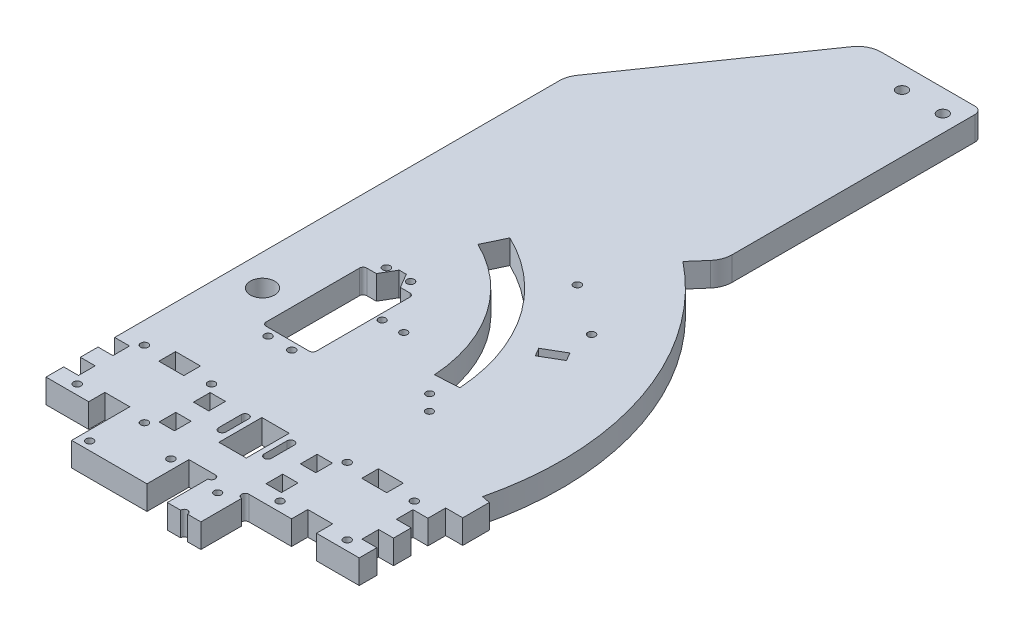
SolidWorks part; units mm, degrees
ref_plane "Płaszczyzna przednia" through (0, 0, 0) normal (0, 0, 1) x (1, 0, 0)
ref_plane "Płaszczyzna górna" through (0, 0, 0) normal (0, 1, 0) x (1, 0, 0)
ref_plane "Płaszczyzna prawa" through (0, 0, 0) normal (1, 0, 0) x (0, 0, -1)
sketch "Szkic1" plane through (0, 0, 0) normal (0, 1, 0) x (1, 0, 0)
  line L1 (0, 0) -> (100, 0)
  line L2 (0, 0) -> (0, 195)
  line L3 (0, 195) -> (100, 195)
  line L4 (100, 0) -> (100, 195)
  dimension "D1" = 100
  dimension "D2" = 195
extrude "Dodanie-wyciągnięcie1" add sketch "Szkic1" along normal blind 10
other "Przenieś ścianę2" face at (50, 5, 0) parameters "D1"=90
other "Przenieś ścianę3" face at (50, 5, -195) parameters "D1"=6.5
sketch "Szkic5" plane through (0, 0, 0) normal (0, -1, 0) x (1, 0, 0)
  line L0 (0, 90) -> (0, -201.5)
  line L1 (0, 90) -> (-538.8713, 90)
  line L2 (0, -201.5) -> (-538.8713, -201.5)
  line L3 (-538.8713, 90) -> (-538.8713, -201.5)
extrude "Dodanie-wyciągnięcie2" add sketch "Szkic5" against normal blind 10
sketch "Szkic6" plane through (0, 10, 0) normal (0, 1, 0) x (1, 0, 0)
  line L0 (100, 201.5) -> (-404.281, 201.5)
  line L1 (100, 201.5) -> (100, -91.9788)
  line L2 (-404.281, 201.5) -> (-404.281, -91.9788)
  line L3 (100, -91.9788) -> (-404.281, -91.9788)
  line L4 (100, 201.5) -> (-538.8713, 201.5) construction
extrude "Wytnij-wyciągnięcie1" cut sketch "Szkic6" against normal blind 10
sketch "Szkic3" plane through (0, 0, 0) normal (0, -1, 0) x (1, 0, 0)
  line L0 (-404.281, -201.5) -> (-404.281, -3.8665)
  line L1 (-486.6766, -104.9667) -> (-486.6766, -201.5)
  line L2 (-486.6766, -201.5) -> (-404.281, -201.5)
  line L5 (-404.281, -201.5) -> (-538.8713, -201.5) construction
  arc A0 (-486.6766, -104.9667) -> (-404.281, -3.8665) centre (-527.8713, 12.7324) ccw
  point P0 (-400.1454, 18.7324)
  dimension "D1" = 249.4
extrude "Wytnij-wyciągnięcie2" cut sketch "Szkic3" against normal blind 10
sketch "Szkic9" plane through (0, 0, 0) normal (0, -1, 0) x (1, 0, 0)
  line L4 (-494.3713, -14.7428) -> (-494.3713, 23.2572) construction
  line L5 (-495.3713, 24.2572) -> (-513.3713, 24.2572) construction
  line L6 (-514.3713, 23.2572) -> (-514.3713, -14.7428) construction
  line L7 (-513.3713, -15.7428) -> (-495.3713, -15.7428) construction
  line L8 (-494.3713, -14.7428) -> (-494.3713, 23.2572)
  line L9 (-495.3713, 24.2572) -> (-513.3713, 24.2572)
  line L10 (-514.3713, 23.2572) -> (-514.3713, -14.7428)
  line L11 (-513.3713, -15.7428) -> (-495.3713, -15.7428)
  line L60 (-513.3713, -16.2428) -> (-495.3713, -16.2428)
  line L61 (-493.8713, -14.7428) -> (-493.8713, 23.2572)
  line L62 (-495.3713, 24.7572) -> (-513.3713, 24.7572)
  line L63 (-514.8713, 23.2572) -> (-514.8713, -14.7428)
  arc A0 (-510.7148, 31.1366) -> (-508.0205, 31.1366) centre (-509.3676, 28.9342) ccw construction
  arc A1 (-500.6957, 31.1375) -> (-498.0469, 31.1375) centre (-499.3713, 29.0172) ccw construction
  arc A2 (-508.0205, -22.6222) -> (-510.7148, -22.6222) centre (-509.3676, -20.4199) ccw construction
  arc A3 (-498.0469, -22.6232) -> (-500.6957, -22.6232) centre (-499.3713, -20.5028) ccw construction
  arc A4 (-510.7148, 31.1366) -> (-508.0205, 31.1366) centre (-509.3676, 28.9342) ccw
  arc A5 (-500.6957, 31.1375) -> (-498.0469, 31.1375) centre (-499.3713, 29.0172) ccw
  arc A6 (-508.0205, -22.6222) -> (-510.7148, -22.6222) centre (-509.3676, -20.4199) ccw
  arc A7 (-498.0469, -22.6232) -> (-500.6957, -22.6232) centre (-499.3713, -20.5028) ccw
  circle A8 centre (-499.3713, 29.0172) radius 1.55
  circle A9 centre (-509.3676, 28.9342) radius 1.55
  circle A10 centre (-499.3713, -20.5028) radius 1.55
  circle A11 centre (-509.3676, -20.4199) radius 1.55
  arc A16 (-494.3713, 23.2572) -> (-495.3713, 24.2572) centre (-495.3713, 23.2572) ccw construction
  arc A17 (-513.3713, 24.2572) -> (-514.3713, 23.2572) centre (-513.3713, 23.2572) ccw construction
  arc A18 (-495.3713, -15.7428) -> (-494.3713, -14.7428) centre (-495.3713, -14.7428) ccw construction
  arc A19 (-514.3713, -14.7428) -> (-513.3713, -15.7428) centre (-513.3713, -14.7428) ccw construction
  arc A20 (-514.3713, -14.7428) -> (-513.3713, -15.7428) centre (-513.3713, -14.7428) ccw
  arc A21 (-494.3713, 23.2572) -> (-495.3713, 24.2572) centre (-495.3713, 23.2572) ccw
  arc A22 (-513.3713, 24.2572) -> (-514.3713, 23.2572) centre (-513.3713, 23.2572) ccw
  arc A23 (-495.3713, -15.7428) -> (-494.3713, -14.7428) centre (-495.3713, -14.7428) ccw
  arc A72 (-514.3713, -14.7428) -> (-513.3713, -15.7428) centre (-513.3713, -14.7428) ccw
  arc A73 (-495.3713, -16.2428) -> (-493.8713, -14.7428) centre (-495.3713, -14.7428) ccw
  arc A74 (-493.8713, 23.2572) -> (-495.3713, 24.7572) centre (-495.3713, 23.2572) ccw
  arc A75 (-513.3713, 24.7572) -> (-514.8713, 23.2572) centre (-513.3713, 23.2572) ccw
  arc A76 (-514.8713, -14.7428) -> (-513.3713, -16.2428) centre (-513.3713, -14.7428) ccw
  dimension "D1" = 3.1
  dimension "D2" = 3.1
  dimension "D3" = 3.1
  dimension "D4" = 3.1
  dimension "D5" = 0.5
  dimension "D6" = 0.5
sketch "Szkic10" plane through (0, 0, 0) normal (0, -1, 0) x (1, 0, 0)
  line L0 (-509.3713, -16.2428) -> (-505.8713, -22.2428)
  line L1 (-513.3713, -16.2428) -> (-495.3713, -16.2428) construction
  line L2 (-493.8713, -14.7428) -> (-493.8713, 23.2572) construction
  line L4 (-514.8713, 23.2572) -> (-514.8713, -14.7428) construction
  line L5 (-513.3713, -16.2428) -> (-509.3713, -16.2428)
  line L6 (-505.8713, -22.2428) -> (-502.8713, -22.2428)
  line L7 (-493.8713, -14.7428) -> (-493.8713, 23.2572)
  line L9 (-514.8713, 23.2572) -> (-514.8713, -14.7428)
  line L10 (-502.8713, -22.2428) -> (-499.3713, -16.2428)
  line L11 (-499.3713, -16.2428) -> (-495.3713, -16.2428)
  line L12 (-513.3713, 25.7572) -> (-495.3713, 25.7572)
  line L13 (-493.8713, 23.2572) -> (-493.8713, 24.2572)
  line L14 (-514.8713, 23.2572) -> (-514.8713, 24.2572)
  circle A0 centre (-499.3713, -20.5028) radius 1.55 construction
  circle A1 centre (-509.3676, -20.4199) radius 1.55 construction
  circle A2 centre (-509.3676, 28.9342) radius 1.55 construction
  circle A3 centre (-499.3713, 29.0172) radius 1.55 construction
  circle A4 centre (-499.3713, -20.5028) radius 1.55
  circle A5 centre (-509.3676, -20.4199) radius 1.55
  circle A6 centre (-509.3676, 28.9342) radius 1.55
  circle A7 centre (-499.3713, 29.0172) radius 1.55
  arc A8 (-493.8713, 24.2572) -> (-495.3713, 25.7572) centre (-495.3713, 24.2572) ccw
  arc A9 (-514.8713, 24.2572) -> (-513.3713, 25.7572) centre (-513.3713, 24.2572) cw
  arc A10 (-495.3713, -16.2428) -> (-493.8713, -14.7428) centre (-495.3713, -14.7428) ccw construction
  arc A15 (-514.8713, -14.7428) -> (-513.3713, -16.2428) centre (-513.3713, -14.7428) ccw construction
  arc A16 (-495.3713, -16.2428) -> (-493.8713, -14.7428) centre (-495.3713, -14.7428) ccw
  arc A19 (-514.8713, -14.7428) -> (-513.3713, -16.2428) centre (-513.3713, -14.7428) ccw
  dimension "D7" = 1.5
  dimension "D1" = 5.5
  dimension "D2" = 5.5
  dimension "D3" = 6
  dimension "D4" = 3.5
  dimension "D5" = 3.5
  dimension "D6" = 42
extrude "Wytnij-wyciągnięcie5" cut sketch "Szkic10" against normal through all
ref_plane "Płaszczyzna1" through (-472.5713, 0, 0) normal (-1, 0, 0) x (0, 0, 1)
sketch "Szkic11" plane through (0, 0, 0) normal (0, -1, 0) x (1, 0, 0)
  line L4 (-494.8713, 75.8884) -> (-500.8713, 75.8884) construction
  line L5 (-500.8713, 75.8884) -> (-500.8713, 82.4384) construction
  line L6 (-500.8713, 82.4384) -> (-494.8713, 82.4384) construction
  line L7 (-494.8713, 82.4384) -> (-494.8713, 75.8884) construction
  line L9 (-522.8713, 60.55) -> (-512.8713, 60.55) construction
  line L10 (-512.8713, 60.55) -> (-512.8713, 54) construction
  line L11 (-512.8713, 54) -> (-522.8713, 54) construction
  line L12 (-500.8713, 68.1116) -> (-494.8713, 68.1116) construction
  line L13 (-494.8713, 68.1116) -> (-494.8713, 61.5616) construction
  line L14 (-494.8713, 61.5616) -> (-500.8713, 61.5616) construction
  line L15 (-500.8713, 61.5616) -> (-500.8713, 68.1116) construction
  line L16 (-522.8713, 83.45) -> (-522.8713, 90)
  line L17 (-522.8713, 90) -> (-512.8713, 90)
  line L18 (-512.8713, 90) -> (-512.8713, 83.45)
  line L19 (-512.8713, 83.45) -> (-522.8713, 83.45)
  line L20 (-494.8713, 75.8884) -> (-500.8713, 75.8884)
  line L21 (-500.8713, 75.8884) -> (-500.8713, 82.4384)
  line L22 (-500.8713, 82.4384) -> (-494.8713, 82.4384)
  line L23 (-494.8713, 82.4384) -> (-494.8713, 75.8884)
  line L24 (-522.8713, 54) -> (-522.8713, 60.55)
  line L25 (-522.8713, 60.55) -> (-512.8713, 60.55)
  line L26 (-512.8713, 60.55) -> (-512.8713, 54)
  line L27 (-512.8713, 54) -> (-522.8713, 54)
  line L28 (-500.8713, 68.1116) -> (-494.8713, 68.1116)
  line L29 (-494.8713, 68.1116) -> (-494.8713, 61.5616)
  line L30 (-494.8713, 61.5616) -> (-500.8713, 61.5616)
  line L31 (-500.8713, 61.5616) -> (-500.8713, 68.1116)
  line L32 (-534.8713, 75.8884) -> (-540.8713, 75.8884) construction
  line L33 (-540.8713, 75.8884) -> (-540.8713, 82.4384) construction
  line L34 (-540.8713, 82.4384) -> (-534.8713, 82.4384) construction
  line L35 (-534.8713, 82.4384) -> (-534.8713, 75.8884) construction
  line L36 (-540.8713, 68.1116) -> (-534.8713, 68.1116) construction
  line L37 (-534.8713, 68.1116) -> (-534.8713, 61.5616) construction
  line L38 (-534.8713, 61.5616) -> (-540.8713, 61.5616) construction
  line L39 (-540.8713, 61.5616) -> (-540.8713, 68.1116) construction
  line L40 (-534.8713, 75.8884) -> (-540.8713, 75.8884)
  line L41 (-540.8713, 75.8884) -> (-540.8713, 82.4384)
  line L42 (-540.8713, 82.4384) -> (-534.8713, 82.4384)
  line L43 (-534.8713, 82.4384) -> (-534.8713, 75.8884)
  line L44 (-540.8713, 68.1116) -> (-534.8713, 68.1116)
  line L45 (-534.8713, 68.1116) -> (-534.8713, 61.5616)
  line L46 (-534.8713, 61.5616) -> (-540.8713, 61.5616)
  line L47 (-540.8713, 61.5616) -> (-540.8713, 68.1116)
  line L48 (-523.0713, 53.8) -> (-523.0713, 60.75)
  line L49 (-523.0713, 60.75) -> (-512.6713, 60.75)
  line L50 (-512.6713, 60.75) -> (-512.6713, 53.8)
  line L51 (-512.6713, 53.8) -> (-523.0713, 53.8)
  line L52 (-534.6713, 68.3116) -> (-534.6713, 61.3616)
  line L53 (-534.6713, 61.3616) -> (-541.0713, 61.3616)
  line L54 (-541.0713, 61.3616) -> (-541.0713, 68.3116)
  line L55 (-541.0713, 68.3116) -> (-534.6713, 68.3116)
  line L56 (-534.6713, 82.6384) -> (-534.6713, 75.6884)
  line L57 (-534.6713, 75.6884) -> (-541.0713, 75.6884)
  line L58 (-541.0713, 75.6884) -> (-541.0713, 82.6384)
  line L59 (-541.0713, 82.6384) -> (-534.6713, 82.6384)
  line L60 (-523.0713, 83.25) -> (-523.0713, 90.2)
  line L61 (-523.0713, 90.2) -> (-512.6713, 90.2)
  line L62 (-512.6713, 90.2) -> (-512.6713, 83.25)
  line L63 (-512.6713, 83.25) -> (-523.0713, 83.25)
  line L64 (-501.0713, 75.6884) -> (-501.0713, 82.6384)
  line L65 (-501.0713, 82.6384) -> (-494.6713, 82.6384)
  line L66 (-494.6713, 82.6384) -> (-494.6713, 75.6884)
  line L67 (-494.6713, 75.6884) -> (-501.0713, 75.6884)
  line L68 (-501.0713, 61.3616) -> (-501.0713, 68.3116)
  line L69 (-501.0713, 68.3116) -> (-494.6713, 68.3116)
  line L70 (-494.6713, 68.3116) -> (-494.6713, 61.3616)
  line L71 (-494.6713, 61.3616) -> (-501.0713, 61.3616)
  line L72 (-522.8713, 90) -> (-522.8713, 83.45) construction
  circle A0 centre (-531.8713, 58) radius 1.55 construction
  circle A1 centre (-419.2913, 58) radius 1.55 construction
  circle A2 centre (-419.2913, 86) radius 1.55 construction
  circle A3 centre (-531.8713, 86) radius 1.55 construction
  circle A4 centre (-531.8713, 58) radius 1.55
  circle A5 centre (-419.2913, 58) radius 1.55
  circle A6 centre (-419.2913, 86) radius 1.55
  circle A7 centre (-531.8713, 86) radius 1.55
  dimension "D2" = 0
  dimension "D1" = 0.2
sketch "Szkic12" plane through (0, 0, 0) normal (0, -1, 0) x (1, 0, 0)
  line L0 (-534.6713, 68.3116) -> (-534.6713, 61.3616) construction
  line L1 (-534.6713, 61.3616) -> (-541.0713, 61.3616) construction
  line L2 (-541.0713, 61.3616) -> (-541.0713, 68.3116) construction
  line L3 (-541.0713, 68.3116) -> (-534.6713, 68.3116) construction
  line L4 (-534.6713, 82.6384) -> (-534.6713, 75.6884) construction
  line L5 (-534.6713, 75.6884) -> (-541.0713, 75.6884) construction
  line L6 (-541.0713, 75.6884) -> (-541.0713, 82.6384) construction
  line L7 (-541.0713, 82.6384) -> (-534.6713, 82.6384) construction
  line L8 (-523.0713, 53.8) -> (-523.0713, 60.75) construction
  line L9 (-523.0713, 60.75) -> (-512.6713, 60.75) construction
  line L10 (-512.6713, 60.75) -> (-512.6713, 53.8) construction
  line L11 (-512.6713, 53.8) -> (-523.0713, 53.8) construction
  line L12 (-523.0713, 83.25) -> (-523.0713, 90.2) construction
  line L13 (-523.0713, 90.2) -> (-512.6713, 90.2) construction
  line L14 (-512.6713, 90.2) -> (-512.6713, 83.25) construction
  line L15 (-512.6713, 83.25) -> (-523.0713, 83.25) construction
  line L16 (-501.0713, 61.3616) -> (-501.0713, 68.3116) construction
  line L17 (-501.0713, 68.3116) -> (-494.6713, 68.3116) construction
  line L18 (-494.6713, 68.3116) -> (-494.6713, 61.3616) construction
  line L19 (-494.6713, 61.3616) -> (-501.0713, 61.3616) construction
  line L20 (-501.0713, 75.6884) -> (-501.0713, 82.6384) construction
  line L21 (-501.0713, 82.6384) -> (-494.6713, 82.6384) construction
  line L22 (-494.6713, 82.6384) -> (-494.6713, 75.6884) construction
  line L23 (-494.6713, 75.6884) -> (-501.0713, 75.6884) construction
  line L24 (-534.6713, 68.3116) -> (-534.6713, 61.3616)
  line L25 (-534.6713, 61.3616) -> (-541.0713, 61.3616)
  line L26 (-541.0713, 61.3616) -> (-541.0713, 68.3116)
  line L27 (-541.0713, 68.3116) -> (-534.6713, 68.3116)
  line L28 (-534.6713, 82.6384) -> (-534.6713, 75.6884)
  line L29 (-534.6713, 75.6884) -> (-541.0713, 75.6884)
  line L30 (-541.0713, 75.6884) -> (-541.0713, 82.6384)
  line L31 (-541.0713, 82.6384) -> (-534.6713, 82.6384)
  line L32 (-523.0713, 53.8) -> (-523.0713, 60.75)
  line L33 (-523.0713, 60.75) -> (-512.6713, 60.75)
  line L34 (-512.6713, 60.75) -> (-512.6713, 53.8)
  line L35 (-512.6713, 53.8) -> (-523.0713, 53.8)
  line L36 (-523.0713, 83.25) -> (-523.0713, 90.2)
  line L37 (-523.0713, 90.2) -> (-512.6713, 90.2)
  line L38 (-512.6713, 90.2) -> (-512.6713, 83.25)
  line L39 (-512.6713, 83.25) -> (-523.0713, 83.25)
  line L40 (-501.0713, 61.3616) -> (-501.0713, 68.3116)
  line L41 (-501.0713, 68.3116) -> (-494.6713, 68.3116)
  line L42 (-494.6713, 68.3116) -> (-494.6713, 61.3616)
  line L43 (-494.6713, 61.3616) -> (-501.0713, 61.3616)
  line L44 (-501.0713, 75.6884) -> (-501.0713, 82.6384)
  line L45 (-501.0713, 82.6384) -> (-494.6713, 82.6384)
  line L46 (-494.6713, 82.6384) -> (-494.6713, 75.6884)
  line L47 (-494.6713, 75.6884) -> (-501.0713, 75.6884)
  line L48 (-475.5761, 90) -> (-475.5761, 36.9235) construction
  line L50 (-456.481, 75.6884) -> (-450.081, 75.6884)
  line L51 (-456.481, 82.6384) -> (-456.481, 75.6884)
  line L52 (-450.081, 82.6384) -> (-456.481, 82.6384)
  line L53 (-450.081, 75.6884) -> (-450.081, 82.6384)
  line L54 (-456.481, 61.3616) -> (-450.081, 61.3616)
  line L55 (-456.481, 68.3116) -> (-456.481, 61.3616)
  line L56 (-450.081, 68.3116) -> (-456.481, 68.3116)
  line L57 (-450.081, 61.3616) -> (-450.081, 68.3116)
  line L58 (-438.481, 83.25) -> (-428.081, 83.25)
  line L59 (-438.481, 90.2) -> (-438.481, 83.25)
  line L60 (-428.081, 90.2) -> (-438.481, 90.2)
  line L61 (-428.081, 83.25) -> (-428.081, 90.2)
  line L62 (-438.481, 53.8) -> (-428.081, 53.8)
  line L63 (-438.481, 60.75) -> (-438.481, 53.8)
  line L64 (-428.081, 60.75) -> (-438.481, 60.75)
  line L65 (-428.081, 53.8) -> (-428.081, 60.75)
  line L66 (-410.081, 82.6384) -> (-416.481, 82.6384)
  line L67 (-410.081, 75.6884) -> (-410.081, 82.6384)
  line L68 (-416.481, 75.6884) -> (-410.081, 75.6884)
  line L69 (-416.481, 82.6384) -> (-416.481, 75.6884)
  line L70 (-410.081, 68.3116) -> (-416.481, 68.3116)
  line L71 (-410.081, 61.3616) -> (-410.081, 68.3116)
  line L72 (-416.481, 61.3616) -> (-410.081, 61.3616)
  line L73 (-416.481, 68.3116) -> (-416.481, 61.3616)
  line L74 (-538.8713, 90) -> (-538.8713, -201.5) construction
  circle A4 centre (-419.2913, 86) radius 1.55 construction
  circle A5 centre (-419.2913, 58) radius 1.55 construction
  circle A6 centre (-531.8713, 86) radius 1.55 construction
  circle A7 centre (-531.8713, 58) radius 1.55 construction
  circle A8 centre (-419.2913, 86) radius 1.55
  circle A9 centre (-419.2913, 58) radius 1.55
  circle A10 centre (-531.8713, 86) radius 1.55
  circle A11 centre (-531.8713, 58) radius 1.55
  circle A12 centre (-447.2913, 86) radius 1.55 construction
  circle A13 centre (-447.2913, 58) radius 1.55 construction
  circle A14 centre (-503.8713, 58) radius 1.55 construction
  circle A15 centre (-503.8713, 86) radius 1.55 construction
  circle A16 centre (-447.2913, 86) radius 1.55
  circle A17 centre (-447.2913, 58) radius 1.55
  circle A18 centre (-503.8713, 58) radius 1.55
  circle A19 centre (-503.8713, 86) radius 1.55
  dimension "D1" = 63.2952
extrude "Wytnij-wyciągnięcie6" cut sketch "Szkic12" against normal blind 10
sketch "Szkic13" plane through (0, 10, 0) normal (0, 1, 0) x (1, 0, 0)
  line L2 (-467.6261, -67.3) -> (-467.6261, -61.3) construction
  line L3 (-467.6261, -75.3) -> (-467.6261, -69.3) construction
  line L4 (-464.5261, -61.3) -> (-464.5261, -67.3) construction
  line L5 (-464.5261, -69.3) -> (-464.5261, -75.3) construction
  line L6 (-470.0761, -61.3) -> (-481.0761, -61.3) construction
  line L7 (-481.0761, -75.3) -> (-470.0761, -75.3) construction
  line L8 (-467.6261, -67.3) -> (-467.6261, -61.3)
  line L9 (-467.6261, -75.3) -> (-467.6261, -69.3)
  line L10 (-464.5261, -61.3) -> (-464.5261, -67.3)
  line L11 (-464.5261, -69.3) -> (-464.5261, -75.3)
  line L12 (-470.0761, -61.3) -> (-481.0761, -61.3)
  line L13 (-481.0761, -75.3) -> (-470.0761, -75.3)
  line L14 (-467.6261, -72.3) -> (-464.5261, -72.3)
  line L15 (-467.6261, -64.3) -> (-464.5261, -64.3)
  line L16 (-481.0761, -75.3) -> (-481.0761, -61.3)
  line L21 (-467.6261, -72.3) -> (-467.6261, -64.3)
  line L22 (-464.5261, -76.9028) -> (-464.5261, -68.9108)
  line L23 (-470.0761, -75.3) -> (-470.0761, -61.3)
  line L24 (-481.2761, -75.5) -> (-469.8761, -75.5)
  line L25 (-469.8761, -75.5) -> (-469.8761, -61.1)
  line L26 (-469.8761, -61.1) -> (-481.2761, -61.1)
  line L27 (-481.2761, -75.5) -> (-481.2761, -61.1)
  line L28 (-486.6261, -69.3) -> (-486.6261, -75.3) construction
  line L29 (-483.5261, -69.3) -> (-483.5261, -75.3) construction
  line L30 (-486.6261, -61.3) -> (-486.6261, -67.3) construction
  line L31 (-483.5261, -61.3) -> (-483.5261, -67.3) construction
  line L32 (-486.6261, -69.3) -> (-486.6261, -75.3)
  line L33 (-483.5261, -69.3) -> (-483.5261, -75.3)
  line L34 (-486.6261, -61.3) -> (-486.6261, -67.3)
  line L35 (-483.5261, -61.3) -> (-483.5261, -67.3)
  line L36 (-486.6261, -72.3) -> (-483.5261, -72.3)
  line L37 (-486.6261, -64.3) -> (-483.5261, -64.3)
  circle A0 centre (-466.0761, -72.3) radius 1.55
  circle A1 centre (-466.0761, -64.3) radius 1.55
  circle A2 centre (-464.5305, -14.7117) radius 10.0739
  circle A3 centre (-485.0761, -72.3) radius 1.55
  circle A4 centre (-485.0761, -64.3) radius 1.55
  dimension "D1" = 3.1
  dimension "D2" = 3.1
  dimension "D4" = 3.1
  dimension "D5" = 3.1
  dimension "D3" = 0.2
sketch "Szkic14" plane through (0, 10, 0) normal (0, 1, 0) x (1, 0, 0)
  line L0 (-469.8761, -75.5) -> (-469.8761, -77.5)
  line L1 (-481.2761, -77.5) -> (-469.8761, -77.5)
  line L2 (-486.6261, -64.3) -> (-486.6261, -62.8)
  line L3 (-483.5261, -64.3) -> (-483.5261, -62.8)
  line L4 (-481.2761, -75.5) -> (-481.2761, -61.1) construction
  line L6 (-469.8761, -75.5) -> (-469.8761, -61.1) construction
  line L7 (-467.6261, -64.3) -> (-467.6261, -62.8)
  line L8 (-467.6261, -72.3) -> (-467.6261, -64.3) construction
  line L9 (-464.5261, -76.9028) -> (-464.5261, -68.9108) construction
  line L10 (-467.6261, -72.3) -> (-467.6261, -64.3)
  line L11 (-464.5261, -72.3) -> (-464.5261, -64.3)
  line L12 (-481.2761, -75.5) -> (-481.2761, -61.1)
  line L13 (-481.2761, -61.1) -> (-481.2761, -59.6)
  line L14 (-469.8761, -75.5) -> (-469.8761, -61.1)
  line L15 (-481.2761, -77.5) -> (-481.2761, -75.5)
  line L16 (-486.6261, -72.3) -> (-486.6261, -64.3)
  line L17 (-483.5261, -72.3) -> (-483.5261, -64.3)
  line L18 (-464.5261, -64.3) -> (-464.5261, -62.8)
  line L19 (-469.8761, -59.6) -> (-481.2761, -59.6)
  line L20 (-469.8761, -59.6) -> (-469.8761, -61.1)
  circle A0 centre (-466.0761, -72.3) radius 1.55 construction
  circle A1 centre (-485.0761, -72.3) radius 1.55 construction
  arc A2 (-467.6261, -72.3) -> (-464.5261, -72.3) centre (-466.0761, -72.3) ccw
  circle A5 centre (-485.0761, -64.3) radius 1.55 construction
  arc A6 (-486.6261, -72.3) -> (-483.5261, -72.3) centre (-485.0761, -72.3) ccw
  circle A7 centre (-466.0761, -64.3) radius 1.55 construction
  arc A8 (-483.5261, -62.8) -> (-486.6261, -62.8) centre (-485.0761, -62.8) ccw
  arc A9 (-464.5261, -62.8) -> (-467.6261, -62.8) centre (-466.0761, -62.8) ccw
  dimension "D1" = 1.5
  dimension "D2" = 1.5
  dimension "D3" = 1.5
  dimension "D4" = 2
extrude "Wytnij-wyciągnięcie7" cut sketch "Szkic14" against normal blind 10
sketch "Szkic15" plane through (0, 0, 0) normal (0, -1, 0) x (-1, 0, 0)
  line L0 (475.5761, -90) -> (475.5761, -31.9756) construction
  line L1 (512.6713, -90) -> (438.481, -90) construction
  line L2 (475.5761, -31.9756) -> (475.5761, -90) construction
sketch "Szkic16" plane through (0, 0, 0) normal (0, -1, 0) x (1, 0, 0)
  line L0 (-460.7106, 8.2055) -> (-450.7332, 7.5329)
  line L1 (-498.7398, -47.9505) -> (-494.4121, -56.9655)
  arc A2 (-494.4121, -56.9655) -> (-450.7332, 7.5329) centre (-527.8713, 12.7324) ccw
  arc A3 (-498.7398, -47.9505) -> (-460.7106, 8.2055) centre (-527.8713, 12.7324) ccw
  point P0 (-527.8713, 12.7324)
  point P1 (-527.8713, 12.7324)
  point P2 (-492.681, -60.5715)
  point P3 (-496.1432, -53.3595)
  point P4 (-456.1497, 27.9252)
  point P5 (-448.3233, 29.5831)
extrude "Wytnij-wyciągnięcie8" cut sketch "Szkic16" against normal blind 10
sketch "Szkic17" plane through (0, 0, 0) normal (0, -1, 0) x (1, 0, 0)
  line L0 (-470.2913, 90) -> (-456.2913, 90)
  line L1 (-470.2913, 90) -> (-470.2913, 110)
  line L2 (-456.2913, 90) -> (-456.2913, 110)
  line L3 (-470.2913, 110) -> (-456.2913, 110)
  line L4 (-512.6713, 90) -> (-438.481, 90) construction
  line L5 (-456.2913, 90) -> (-456.2913, 82.4384) construction
  line L6 (-481.2761, 107.5) -> (-512.6713, 107.5)
  line L7 (-481.2761, 90) -> (-512.6713, 90)
  line L8 (-481.2761, 90) -> (-481.2761, 107.5)
  line L9 (-512.6713, 90) -> (-512.6713, 107.5)
  line L13 (-512.6713, 83.25) -> (-512.6713, 90) construction
  dimension "D1" = 0
  dimension "D2" = 20
  dimension "D3" = 14
  dimension "D4" = 17.5
  dimension "D5" = 31.3952
  dimension "D6" = 0
extrude "Dodanie-wyciągnięcie3" add sketch "Szkic17" against normal blind 10
sketch "Szkic18" plane through (0, 0, 0) normal (0, -1, 0) x (1, 0, 0)
  circle A1 centre (-450.9064, -49.5364) radius 3
sketch "Szkic19" plane through (0, 0, 0) normal (0, -1, 0) x (1, 0, 0)
  circle A0 centre (-527.8713, 12.7324) radius 5.05 construction
  circle A1 centre (-527.8713, 12.7324) radius 5.05
extrude "Wytnij-wyciągnięcie10" cut sketch "Szkic19" against normal blind 10
sketch "Szkic20" plane through (0, 0, 0) normal (0, -1, 0) x (1, 0, 0)
  line L0 (-538.8713, 53.8) -> (-538.9213, 53.8)
  line L1 (-538.8713, 61.3616) -> (-538.8713, -201.5) construction
  line L2 (-540.8713, 51.85) -> (-540.8713, -199.55)
  line L3 (-538.9213, -201.5) -> (-538.8713, -201.5)
  line L4 (-538.8713, -201.5) -> (-538.8713, 53.8)
  line L5 (-523.0713, 53.8) -> (-512.6713, 53.8) construction
  arc A0 (-540.8713, -199.55) -> (-538.9213, -201.5) centre (-538.9213, -199.55) ccw
  arc A1 (-538.9213, 53.8) -> (-540.8713, 51.85) centre (-538.9213, 51.85) ccw
  dimension "D3" = 1.95
  dimension "D1" = 2
  dimension "D2" = 0
extrude "Dodanie-wyciągnięcie4" add sketch "Szkic20" against normal blind 10 separate body
combine bodies "Połącz1" operation type add bodies to combine 124 123
sketch "Szkic22" plane through (0, 10, 0) normal (0, 1, 0) x (1, 0, 0)
  line L0 (-486.6766, 201.5) -> (-477.6766, 201.5)
  line L1 (-475.6766, 199.5) -> (-475.6766, 114.8256)
  line L2 (-440.9781, 88.2026) -> (-440.0828, 89.1525)
  line L3 (-486.6766, 104.9667) -> (-486.6766, 201.5)
  line L8 (-440.9781, 88.2026) -> (-448.3145, 80.4192)
  line L9 (-448.3145, 80.4192) -> (-486.6766, 104.9667)
  arc A0 (-404.281, 3.8665) -> (-486.6766, 104.9667) centre (-527.8713, -12.7324) ccw construction
  arc A1 (-477.6766, 201.5) -> (-475.6766, 199.5) centre (-477.6766, 199.5) cw
  arc A2 (-474.4586, 112.9848) -> (-475.6766, 114.8256) centre (-473.6766, 114.8256) cw
  arc A3 (-440.0828, 89.1525) -> (-440.2553, 92.0587) centre (-441.5381, 90.5243) ccw
  arc A4 (-474.4586, 112.9848) -> (-440.2553, 92.0587) centre (-527.8713, -12.7324) cw
  point P18 (-440.2504, 87.5167)
  point P20 (-452.5967, 74.4182)
  point P22 (-453.3244, 75.1041)
  dimension "D2" = 2
  dimension "D3" = 2
  dimension "D4" = 2
  dimension "D1" = 11
extrude "Dodanie-wyciągnięcie5" add sketch "Szkic22" against normal blind 10
sketch "Szkic23" plane through (0, 0, 0) normal (0, -1, 0) x (-1, 0, 0)
  line L0 (538.8713, -90) -> (540.8713, -90)
  line L1 (540.8713, -90) -> (540.8713, -82.6384)
  line L2 (540.8713, -82.6384) -> (538.8713, -82.6384)
  line L3 (538.8713, -82.6384) -> (538.8713, -90)
  line L4 (538.8713, -75.6884) -> (540.8713, -75.6884)
  line L5 (538.8713, -75.6884) -> (538.8713, -68.3116)
  line L6 (540.8713, -75.6884) -> (540.8713, -68.3116)
  line L7 (538.8713, -68.3116) -> (540.8713, -68.3116)
  line L8 (538.8713, -61.3616) -> (540.8713, -61.3616)
  line L9 (540.8713, -61.3616) -> (540.8713, -51.85)
  line L10 (540.8713, -51.85) -> (538.8713, -53.8)
  line L11 (538.8713, -53.8) -> (538.8713, -61.3616)
  line L12 (534.6713, -68.3116) -> (538.8713, -68.3116) construction
  dimension "D1" = 0
extrude "Dodanie-wyciągnięcie6" add sketch "Szkic23" against normal blind 10
sketch "Szkic24" plane through (0, 10, 0) normal (0, 1, 0) x (1, 0, 0)
  arc A0 (-404.281, 3.8665) -> (-409.8648, -53.0383) centre (-527.8713, -12.7324) cw
sketch "Szkic25" plane through (0, 10, 0) normal (0, 1, 0) x (1, 0, 0)
  line L0 (-404.281, 3.8665) -> (-404.281, -29.3314)
  arc A0 (-409.8648, -53.0383) -> (-404.281, 3.8665) centre (-527.8713, -12.7324) ccw construction
  arc A1 (-404.281, -29.3314) -> (-404.281, 3.8665) centre (-527.8713, -12.7324) ccw
extrude "Dodanie-wyciągnięcie7" add sketch "Szkic25" against normal blind 10
sketch "Szkic26" plane through (0, 10, 0) normal (0, 1, 0) x (1, 0, 0)
  line L0 (-399.9995, -49.9762) -> (-396.142, -50.9135)
  line L3 (-404.281, -29.3314) -> (-395.7395, -31.6227)
  line L4 (-395.7395, -31.6227) -> (-396.142, -50.9135)
  line L7 (-399.9995, -49.9762) -> (-408.2538, -47.9707)
  arc A0 (-409.8648, -53.0383) -> (-404.281, 3.8665) centre (-527.8713, -12.7324) ccw construction
  arc A4 (-408.2538, -47.9707) -> (-404.281, -29.3314) centre (-527.8713, -12.7324) ccw
  point P1 (-399.7634, -49.0045)
  point P11 (-417.2545, -44.7547)
extrude "Wytnij-wyciągnięcie14" cut sketch "Szkic26" against normal blind 10
sketch "Szkic27" plane through (0, 0, 0) normal (0, -1, 0) x (1, 0, 0)
  circle A0 centre (-508.6761, 104) radius 1.55 construction
  circle A1 centre (-485.2761, 93.5) radius 1.55 construction
  circle A2 centre (-508.6761, 104) radius 1.55
  circle A3 centre (-485.2761, 93.5) radius 1.55
extrude "Wytnij-wyciągnięcie15" cut sketch "Szkic27" against normal blind 10
sketch "Szkic28" plane through (0, 10, 0) normal (0, 1, 0) x (1, 0, 0)
  circle A0 centre (-463.3839, 54.0753) radius 1.55 construction
  circle A1 centre (-442.5371, 39.1347) radius 1.55 construction
  circle A2 centre (-463.3839, 54.0753) radius 1.55
  circle A3 centre (-442.5371, 39.1347) radius 1.55
extrude "Wytnij-wyciągnięcie16" cut sketch "Szkic28" against normal blind 10
sketch "Szkic29" plane through (0, 0, 0) normal (0, -1, 0) x (1, 0, 0)
  line L0 (-440.3446, -27.9144) -> (-438.3322, -24.4575)
  line L1 (-440.3446, -27.9144) -> (-448.5548, -23.135)
  line L2 (-438.3322, -24.4575) -> (-446.5424, -19.6781)
  line L3 (-448.5548, -23.135) -> (-446.5424, -19.6781)
  line L5 (-449.1577, -41.0662) -> (-447.6484, -38.4735) construction
  line L6 (-454.1301, -34.7003) -> (-455.6394, -37.293) construction
  line L7 (-448.4034, -31.3228) -> (-447.5392, -31.8259) construction
  dimension "D1" = 1
  dimension "D2" = 1
  dimension "D3" = 7
  dimension "D4" = 4
extrude "Wytnij-wyciągnięcie17" cut sketch "Szkic29" against normal blind 10
sketch "Szkic32" plane through (0, 10, 0) normal (0, 1, 0) x (1, 0, 0)
  line L0 (-404.281, -90) -> (-410.281, -90)
  line L1 (-404.281, -90) -> (-404.281, -53.936)
  line L2 (-410.281, -90) -> (-410.281, -53.936)
  line L3 (-404.281, -53.936) -> (-410.281, -53.936)
  line L4 (-428.081, -90) -> (-404.281, -90) construction
  dimension "D1" = 5
  dimension "D2" = 6
extrude "Wytnij-wyciągnięcie18" cut sketch "Szkic32" against normal blind 10
sketch "Szkic33" plane through (0, 0, 0) normal (0, -1, 0) x (-1, 0, 0)
  line L0 (493.8713, 14.7428) -> (493.8713, -24.2572) construction
  line L2 (493.8713, 14.7428) -> (493.8713, -24.2572) construction
  circle A0 centre (454.8713, -16.0322) radius 1.5
  circle A1 centre (448.5626, -22.451) radius 1.5
  circle A2 centre (491.3713, 0.6743) radius 1.5
  circle A3 centre (482.3713, 0.6743) radius 1.5
  arc A4 (503.94, 12.16) -> (504.8026, 12.16) centre (504.3713, 5.6743) ccw construction
  dimension "D1" = 3
  dimension "D2" = 3
  dimension "D3" = 9
  dimension "D4" = 3
  dimension "D5" = 3
  dimension "D6" = 9
  dimension "D7" = 2.5
  dimension "D8" = 5
  dimension "D9" = 6.3087
  dimension "D10" = 39
extrude "Wytnij-wyciągnięcie19" cut sketch "Szkic33" against normal blind 10
sketch "Szkic34" plane through (0, 0, 0) normal (0, -1, 0) x (1, 0, 0)
  line L0 (-456.2913, 90) -> (-456.2913, 110) construction
  line L1 (-470.2913, 110) -> (-470.2913, 90) construction
  line L2 (-481.2761, 90) -> (-470.2913, 90) construction
  line L3 (-456.2913, 90) -> (-438.481, 90) construction
  circle A0 centre (-456.2913, 91.5) radius 1.5
  circle A1 centre (-470.2913, 91.5) radius 1.5
  dimension "D1" = 3
  dimension "D2" = 3
  dimension "D3" = 1.5
  dimension "D4" = 1.5
extrude "Wytnij-wyciągnięcie20" cut sketch "Szkic34" against normal blind 10
sketch "Szkic35" plane through (0, 10, 0) normal (0, 1, 0) x (1, 0, 0)
  line L0 (-408.2538, -47.9707) -> (-404.281, -48.936)
  line L1 (-404.281, -53.936) -> (-404.281, -48.936)
  line L3 (-446.8045, 82.0213) -> (-440.0828, 89.1525)
  line L4 (-403.1713, -42.8713) -> (-403.1713, -53.936)
  line L5 (-437.853, 90.0025) -> (-446.0192, 81.3438)
  line L7 (-403.1713, -42.8713) -> (-406.6942, -42.1639)
  line L8 (-404.281, -53.936) -> (-403.1713, -53.936)
  arc A2 (-408.2538, -47.9707) -> (-406.6942, -42.1639) centre (-527.8713, -12.7324) ccw
  arc A3 (-437.853, 90.0025) -> (-440.2553, 92.0587) centre (-527.8713, -12.7324) ccw
  arc A6 (-440.0828, 89.1525) -> (-440.2553, 92.0587) centre (-441.5381, 90.5243) ccw
  arc A8 (-446.0192, 81.3438) -> (-446.8045, 82.0213) centre (-527.8713, -12.7324) ccw
  point P4 (-403.1027, -42.9872)
  point P12 (-406.7808, -42.0953)
extrude "Dodanie-wyciągnięcie8" add sketch "Szkic35" against normal blind 10
sketch "Szkic36" plane through (0, 10, 0) normal (0, 1, 0) x (1, 0, 0)
  line L0 (-456.2913, -110) -> (-470.2913, -110) construction
  circle A0 centre (-463.2913, -96) radius 1.5
  circle A1 centre (-463.2913, -110) radius 1.5
  dimension "D1" = 0
  dimension "D2" = 14
  dimension "D3" = 3
  dimension "D4" = 3
extrude "Wytnij-wyciągnięcie21" cut sketch "Szkic36" against normal blind 10
sketch "Szkic37" plane through (0, 10, 0) normal (0, 1, 0) x (1, 0, 0)
  line L1 (-441.4807, 94.1) -> (-449.8211, 84.5211)
  line L2 (-437.853, 90.0025) -> (-441.4807, 94.1)
  line L3 (-437.853, 90.0025) -> (-446.0192, 81.3438)
  arc A1 (-446.0192, 81.3438) -> (-449.8211, 84.5211) centre (-527.8713, -12.7324) ccw
extrude "Wytnij-wyciągnięcie22" cut sketch "Szkic37" against normal blind 10
sketch "Szkic38" plane through (0, 10, 0) normal (0, 1, 0) x (1, 0, 0)
  line L0 (-442.0053, 93.4974) -> (-442.0053, 198.5)
  line L1 (-477.6766, 201.5) -> (-445.0053, 201.5)
  line L2 (-475.6766, 114.8256) -> (-475.6766, 199.5) construction
  line L3 (-475.6766, 114.8256) -> (-475.6766, 199.5)
  arc A0 (-475.6766, 199.5) -> (-477.6766, 201.5) centre (-477.6766, 199.5) ccw construction
  arc A1 (-475.6766, 114.8256) -> (-474.4586, 112.9848) centre (-473.6766, 114.8256) ccw construction
  arc A3 (-475.6766, 199.5) -> (-477.6766, 201.5) centre (-477.6766, 199.5) ccw
  arc A4 (-475.6766, 114.8256) -> (-474.4586, 112.9848) centre (-473.6766, 114.8256) ccw
  arc A6 (-445.0053, 201.5) -> (-442.0053, 198.5) centre (-445.0053, 198.5) cw
  arc A7 (-442.0053, 93.4974) -> (-474.4586, 112.9848) centre (-527.8713, -12.7324) ccw construction
  arc A8 (-442.0053, 93.4974) -> (-474.4586, 112.9848) centre (-527.8713, -12.7324) ccw
  dimension "D1" = 3
extrude "Dodanie-wyciągnięcie9" add sketch "Szkic38" against normal blind 10
sketch "Szkic8" plane through (0, 0, 0) normal (0, -1, 0) x (1, 0, 0)
  circle A0 centre (-466.0553, -192.1) radius 2.25 construction
  circle A1 centre (-449.0553, -192.1) radius 2.25 construction
  circle A2 centre (-466.0553, -192.1) radius 2.25
  circle A3 centre (-449.0553, -192.1) radius 2.25
extrude "Wytnij-wyciągnięcie4" cut sketch "Szkic8" against normal through all
sketch "Szkic39" plane through (0, 0, 0) normal (0, -1, 0) x (1, 0, 0)
  line L1 (-538.9213, -201.5) -> (-484.0397, -201.5)
  line L4 (-539.0868, -129.7179) -> (-492.2552, -197.2013)
  line L5 (-540.8713, -199.55) -> (-540.8713, -124.0166)
  arc A1 (-540.8713, -199.55) -> (-538.9213, -201.5) centre (-538.9213, -199.55) ccw
  arc A2 (-492.2552, -197.2013) -> (-484.0397, -201.5) centre (-484.0397, -191.5) ccw
  arc A4 (-539.0868, -129.7179) -> (-540.8713, -124.0166) centre (-530.8713, -124.0166) cw
  dimension "D1" = 10
  dimension "D2" = 10
extrude "Wytnij-wyciągnięcie23" cut sketch "Szkic39" against normal blind 10
sketch "Szkic40" plane through (0, 0, 0) normal (0, -1, 0) x (1, 0, 0)
  line L4 (-442.0053, -97.2409) -> (-442.0053, -93.4974)
  line L5 (-442.0053, -93.4974) -> (-444.4635, -90.6742)
  arc A0 (-444.4635, -90.6742) -> (-442.0053, -97.2409) centre (-452.0053, -97.2409) cw
  dimension "D1" = 10
extrude "Wytnij-wyciągnięcie24" cut sketch "Szkic40" against normal blind 10
equation "\"tolerancja_wpusy\"=0.2"
equation "\"dlugosc_wpustu_duzy\"=20"
equation "\"srednica_otworu_M3\"=3.1"
equation "\"D1@Szkic9\"=\"srednica_otworu_M3\""
equation "\"szerokosc_nogi_T\"=3.1"
equation "\"dlugosc_T_30\"=11"
equation "\"grubosc_na_nakretke_kwadrat\"=2"
equation "\"szerokosc_na_nakretke_kwadrat\"=5.85"
equation "\"wyokosc_nadstawki_T\"=0.5"
equation "\"dlugosc_T_20_6\"=14"
equation "\"D2@Szkic9\"=\"srednica_otworu_M3\""
equation "\"D3@Szkic9\"=\"srednica_otworu_M3\""
equation "\"D4@Szkic9\"=\"srednica_otworu_M3\""
equation "\"D1@Szkic13\"=\"srednica_otworu_M3\""
equation "\"D2@Szkic13\"=\"srednica_otworu_M3\""
equation "\"D4@Szkic13\"=\"srednica_otworu_M3\""
equation "\"D5@Szkic13\"=\"srednica_otworu_M3\""
